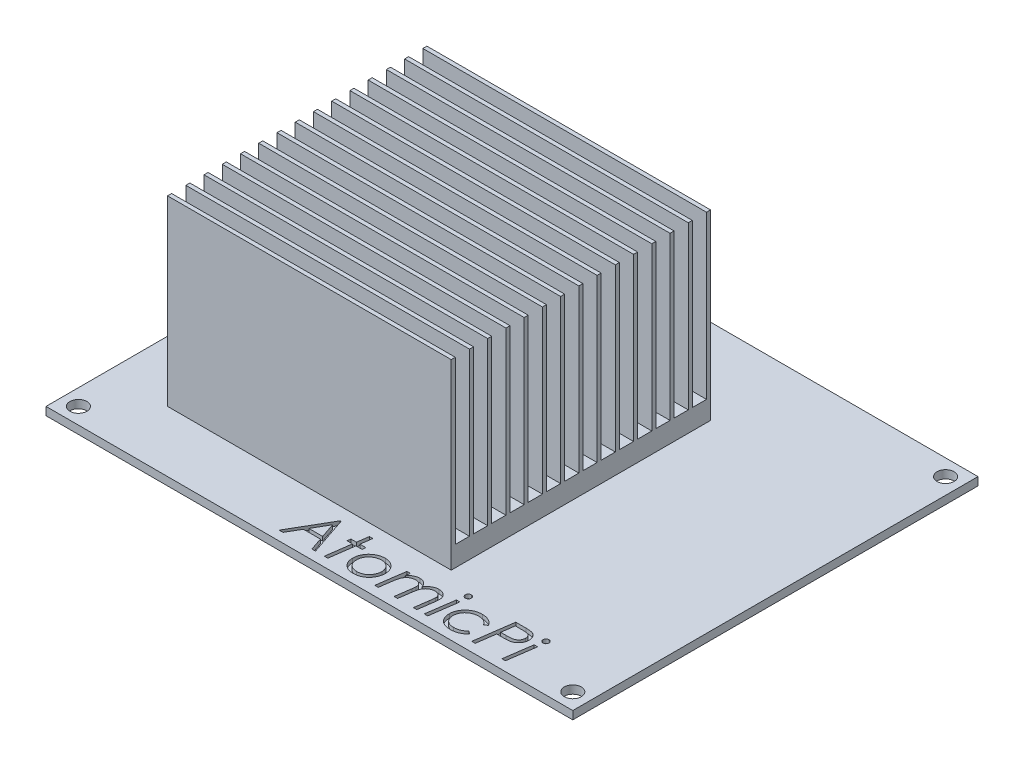
SolidWorks part; units mm, degrees
ref_plane "Front Plane" through (0, 0, 0) normal (0, 0, 1) x (1, 0, 0)
ref_plane "Top Plane" through (0, 0, 0) normal (0, 1, 0) x (1, 0, 0)
ref_plane "Right Plane" through (0, 0, 0) normal (1, 0, 0) x (0, 0, -1)
sketch "Sketch1" plane through (0, 0, 0) normal (0, 1, 0) x (1, 0, 0)
  line L1 (-65, -50) -> (65, -50)
  line L2 (-65, -50) -> (-65, 50)
  line L3 (-65, 50) -> (65, 50)
  line L4 (65, -50) -> (65, 50)
  line L5 (-65, -50) -> (65, 50) construction
  line L6 (-65, 50) -> (65, -50) construction
  circle A0 centre (-61, 46) radius 2.1
  circle A1 centre (61, 46) radius 2.1
  circle A2 centre (-61, -46) radius 2.1
  circle A3 centre (61, -46) radius 2.1
  point P0 (0, 0)
  dimension "D3" = 4.2
  dimension "D8" = 122
  dimension "D1" = 130
  dimension "D2" = 100
  dimension "D4" = 4
  dimension "D5" = 4
  dimension "D9" = 92
  dimension "D6" = 2
  dimension "D7" = 2
extrude "Boss-Extrude1" add sketch "Sketch1" along normal blind 2
sketch "Sketch2" plane through (0, 2, 0) normal (0, 1, 0) x (1, 0, 0)
  line L0 (-65, 50) -> (-65, -50) construction
  line L1 (-65, -50) -> (65, -50) construction
  line L2 (-50, -35) -> (20, -35)
  line L3 (-50, -35) -> (-50, 29)
  line L4 (-50, 29) -> (20, 29)
  line L5 (20, -35) -> (20, 29)
  line L6 (-50, -35) -> (20, 29) construction
  line L7 (-50, 29) -> (20, -35) construction
  point P0 (-15, -3)
  dimension "D1" = 64
  dimension "D2" = 70
  dimension "D3" = 15
  dimension "D4" = 15
extrude "Boss-Extrude2" add sketch "Sketch2" along normal blind 45
sketch "Sketch3" plane through (0, 0, 0) normal (0, -1, 0) x (1, 0, 0)
  line L0 (-65, -50) -> (-65, 50) construction
  line L1 (-65, 31.3276) -> (-59.1086, 31.3276)
  line L2 (-65, 31.3276) -> (-65, 0)
  line L3 (-65, 0) -> (-59.1086, 0)
  line L4 (-59.1086, 31.3276) -> (-59.1086, 0)
extrude "Boss-Extrude3" add sketch "Sketch3" along normal blind 10
sketch "Sketch4" plane through (0, 47, 0) normal (0, 1, 0) x (1, 0, 0)
  text T0 "AtomicPi" font "Century Gothic" height in points 36
extrude "Cut-Extrude1" cut sketch "Sketch4" against normal blind 46
sketch "Sketch5" plane through (0, 47, 0) normal (0, 1, 0) x (1, 0, 0)
  line L0 (-50, 29) -> (-50, -35) construction
  line L1 (-50, 28) -> (20, 28)
  line L2 (-50, 28) -> (-50, 24.5)
  line L3 (-50, 24.5) -> (20, 24.5)
  line L4 (20, 28) -> (20, 24.5)
  line L5 (20, -35) -> (20, 29) construction
  line L6 (20, 29) -> (-50, 29) construction
  line L7 (-50, 23.5) -> (-50, 20)
  line L8 (-50, 23.5) -> (20, 23.5)
  line L9 (20, 23.5) -> (20, 20)
  line L10 (-50, 20) -> (20, 20)
  line L11 (-50, 19) -> (-50, 15.5)
  line L12 (-50, 19) -> (20, 19)
  line L13 (20, 19) -> (20, 15.5)
  line L14 (-50, 15.5) -> (20, 15.5)
  line L15 (-50, 14.5) -> (-50, 11)
  line L16 (-50, 14.5) -> (20, 14.5)
  line L17 (20, 14.5) -> (20, 11)
  line L18 (-50, 11) -> (20, 11)
  line L19 (-50, 10) -> (-50, 6.5)
  line L20 (-50, 10) -> (20, 10)
  line L21 (20, 10) -> (20, 6.5)
  line L22 (-50, 6.5) -> (20, 6.5)
  line L23 (-50, 5.5) -> (-50, 2)
  line L24 (-50, 5.5) -> (20, 5.5)
  line L25 (20, 5.5) -> (20, 2)
  line L26 (-50, 2) -> (20, 2)
  line L27 (-50, 1) -> (-50, -2.5)
  line L28 (-50, 1) -> (20, 1)
  line L29 (20, 1) -> (20, -2.5)
  line L30 (-50, -2.5) -> (20, -2.5)
  line L31 (-50, -3.5) -> (-50, -7)
  line L32 (-50, -3.5) -> (20, -3.5)
  line L33 (20, -3.5) -> (20, -7)
  line L34 (-50, -7) -> (20, -7)
  line L35 (-50, -8) -> (-50, -11.5)
  line L36 (-50, -8) -> (20, -8)
  line L37 (20, -8) -> (20, -11.5)
  line L38 (-50, -11.5) -> (20, -11.5)
  line L39 (-50, -12.5) -> (-50, -16)
  line L40 (-50, -12.5) -> (20, -12.5)
  line L41 (20, -12.5) -> (20, -16)
  line L42 (-50, -16) -> (20, -16)
  line L43 (-50, -17) -> (-50, -20.5)
  line L44 (-50, -17) -> (20, -17)
  line L45 (20, -17) -> (20, -20.5)
  line L46 (-50, -20.5) -> (20, -20.5)
  line L47 (-50, -21.5) -> (-50, -25)
  line L48 (-50, -21.5) -> (20, -21.5)
  line L49 (20, -21.5) -> (20, -25)
  line L50 (-50, -25) -> (20, -25)
  line L51 (-50, -26) -> (-50, -29.5)
  line L52 (-50, -26) -> (20, -26)
  line L53 (20, -26) -> (20, -29.5)
  line L54 (-50, -29.5) -> (20, -29.5)
  line L59 (-50, -30.5) -> (-50, -34)
  line L60 (-50, -30.5) -> (20, -30.5)
  line L61 (20, -30.5) -> (20, -34)
  line L62 (-50, -34) -> (20, -34)
  dimension "D1" = 1
  dimension "D2" = 3.5
  dimension "D4" = 1
  dimension "D3" = 14
extrude "Cut-Extrude2" cut sketch "Sketch5" against normal blind 40
sketch "Sketch6" plane through (0, 0, -50) normal (0, 0, -1) x (-1, 0, 0)
  line L0 (-65, 2) -> (65, 2) construction
  line L1 (55, 2) -> (40, 2)
  line L2 (55, 2) -> (55, 8)
  line L3 (55, 8) -> (40, 8)
  line L4 (40, 2) -> (40, 8)
  line L5 (65, 2) -> (65, 0) construction
  dimension "D1" = 10
  dimension "D2" = 15
  dimension "D3" = 6
extrude "Boss-Extrude4" add sketch "Sketch6" against normal blind 12
sketch "Sketch7" plane through (0, 8, 0) normal (0, 1, 0) x (1, 0, 0)
  text T0 "HDMI"
extrude "Cut-Extrude3" cut sketch "Sketch7" against normal blind 1
